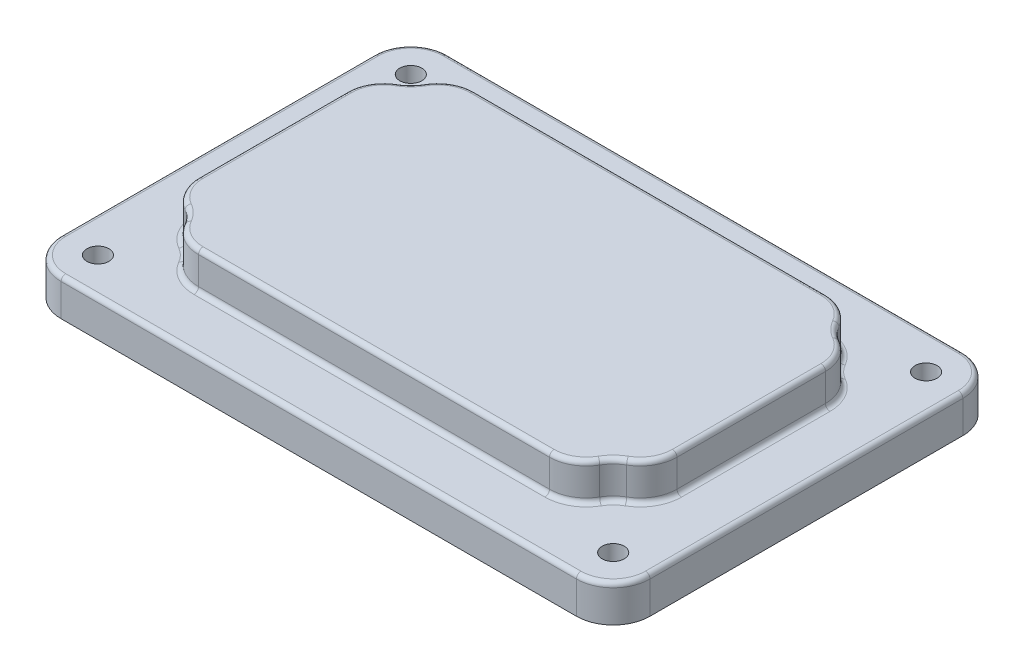
SolidWorks part; units mm, degrees
material "Cast Alloy Steel"
ref_plane "Front Plane" through (0, 0, 0) normal (0, 0, 1) x (1, 0, 0)
ref_plane "Top Plane" through (0, 0, 0) normal (0, 1, 0) x (1, 0, 0)
ref_plane "Right Plane" through (0, 0, 0) normal (1, 0, 0) x (0, 0, -1)
sketch "Sketch1" plane through (0, 0, 0) normal (0, 1, 0) x (1, 0, 0)
  line L1 (-44.45, 33.3375) -> (44.45, 33.3375)
  line L2 (-50.8, 26.9875) -> (-50.8, -26.9875)
  line L3 (-44.45, -33.3375) -> (44.45, -33.3375)
  line L4 (50.8, 26.9875) -> (50.8, -26.9875)
  line L5 (-50.8, 33.3375) -> (50.8, -33.3375) construction
  line L6 (-50.8, -33.3375) -> (50.8, 33.3375) construction
  arc A0 (44.45, -33.3375) -> (50.8, -26.9875) centre (44.45, -26.9875) ccw
  arc A1 (44.45, 33.3375) -> (50.8, 26.9875) centre (44.45, 26.9875) cw
  arc A2 (-44.45, 33.3375) -> (-50.8, 26.9875) centre (-44.45, 26.9875) ccw
  arc A3 (-50.8, -26.9875) -> (-44.45, -33.3375) centre (-44.45, -26.9875) ccw
  point P0 (0, 0)
  dimension "D3" = 6.35
  dimension "D1" = 66.675
  dimension "D2" = 101.6
extrude "Base" add sketch "Sketch1" along normal blind 6.35
sketch "Sketch2" plane through (0, 6.35, 0) normal (0, 1, 0) x (1, 0, 0)
  line L8 (41.275, -23.8125) -> (41.275, 23.8125)
  line L9 (41.275, 23.8125) -> (-41.275, 23.8125)
  line L10 (-41.275, 23.8125) -> (-41.275, -23.8125)
  line L11 (-41.275, -23.8125) -> (41.275, -23.8125)
  line L12 (41.275, -23.8125) -> (41.275, 23.8125)
  line L13 (41.275, 23.8125) -> (-41.275, 23.8125)
  line L14 (-41.275, 23.8125) -> (-41.275, -23.8125)
  line L15 (-41.275, -23.8125) -> (41.275, -23.8125)
  dimension "D1" = 9.525
extrude "Top Boss" add sketch "Sketch2" along normal blind 6.35
sketch "Sketch3" plane through (0, 12.7, 0) normal (0, 1, 0) x (1, 0, 0)
  line L0 (0, 0) -> (60.3016, 0) construction
  line L1 (0, 0) -> (0, 40.0067) construction
  circle A0 centre (41.275, 23.8125) radius 6.35
  circle A1 centre (-41.275, 23.8125) radius 6.35
  circle A2 centre (-41.275, -23.8125) radius 6.35
  circle A3 centre (41.275, -23.8125) radius 6.35
  dimension "D1" = 12.7
extrude "Corner Cuts" cut sketch "Sketch3" against normal up to surface (6.35 mm away) up to face at (0, 6.35, 0)
fillet "Fillet1" radius 6.35 8 edges at (34.925, 9.525, 23.8125) (41.275, 9.525, 17.4625) (41.275, 9.525, -17.4625) (34.925, 9.525, -23.8125) (-34.925, 9.525, -23.8125) (-41.275, 9.525, -17.4625) (-41.275, 9.525, 17.4625) (-34.925, 9.525, 23.8125)
shell "Shell1" thickness 3.175
sketch "Sketch4" plane through (0, 0, 0) normal (0, -1, 0) x (1, 0, 0)
  circle A0 centre (-44.45, 26.9875) radius 6.35
  circle A1 centre (44.45, 26.9875) radius 6.35
  circle A2 centre (44.45, -26.9875) radius 6.35
  circle A3 centre (-44.45, -26.9875) radius 6.35
  arc A4 (-50.8, -26.9875) -> (-44.45, -33.3375) centre (-44.45, -26.9875) ccw construction
extrude "Boss-Extrude3" add sketch "Sketch4" against normal up to surface (3.175 mm away) up to face at (0, 3.175, 0)
fillet "Fillet2" radius 0.7874 40 edges at (0, 6.35, 33.3375) (-48.9401, 6.35, 31.4776) (-50.8, 6.35, 0) (-48.9401, 6.35, -31.4776) (0, 6.35, -33.3375) (48.9401, 6.35, -31.4776) (50.8, 6.35, 0) (48.9401, 6.35, 31.4776) (-40.4243, 6.35, 15.989) (-36.7849, 12.7, 19.3224) (-36.7849, 6.35, 19.3224) (-33.4515, 6.35, 22.9618) (0, 6.35, 23.8125) (33.4515, 6.35, 22.9618) (36.7849, 12.7, 19.3224) (36.7849, 6.35, 19.3224) (40.4243, 6.35, 15.989) (41.275, 6.35, 0) (40.4243, 6.35, -15.989) (36.7849, 12.7, -19.3224) (36.7849, 6.35, -19.3224) (33.4515, 6.35, -22.9618) (0, 6.35, -23.8125) (-33.4515, 6.35, -22.9618) (-36.7849, 12.7, -19.3224) (-36.7849, 6.35, -19.3224) (-40.4243, 6.35, -15.989) (-41.275, 6.35, 0) (-33.4515, 12.7, 22.9618) (-40.4243, 12.7, 15.989) (-41.275, 12.7, 0) (-40.4243, 12.7, -15.989) (-33.4515, 12.7, -22.9618) (0, 12.7, -23.8125) (33.4515, 12.7, -22.9618) (40.4243, 12.7, -15.989) (41.275, 12.7, 0) (40.4243, 12.7, 15.989) (33.4515, 12.7, 22.9618) (0, 12.7, 23.8125)
fillet "Fillet3" radius 0.7874 56 edges at (39.9599, 0, -22.4974) (39.9599, 3.175, -22.4974) (-39.9599, 0, -22.4974) (-39.9599, 3.175, -22.4974) (-39.9599, 0, 22.4974) (-39.9599, 3.175, 22.4974) (39.9599, 3.175, 22.4974) (39.9599, 0, 22.4974) (47.625, 3.175, 0) (47.625, 1.5875, 21.4882) (47.625, 0, 0) (47.625, 1.5875, -21.4882) (0, 3.175, -30.1625) (38.9507, 1.5875, -30.1625) (0, 0, -30.1625) (-38.9507, 1.5875, -30.1625) (-47.625, 0, 0) (-47.625, 1.5875, 21.4882) (-47.625, 3.175, 0) (-47.625, 1.5875, -21.4882) (0, 3.175, 30.1625) (-38.9507, 1.5875, 30.1625) (0, 0, 30.1625) (38.9507, 1.5875, 30.1625) (0, 3.175, 20.6375) (38.1, 3.175, 0) (0, 3.175, -20.6375) (-38.1, 3.175, 0) (38.1, 9.525, 0) (0, 9.525, -20.6375) (-38.1, 9.525, 0) (0, 9.525, 20.6375) (34.5398, 3.175, -17.0773) (34.5398, 9.525, -17.0773) (34.5398, 3.175, 17.0773) (34.5398, 9.525, 17.0773) (-34.5398, 3.175, 17.0773) (-34.5398, 9.525, 17.0773) (-34.5398, 3.175, -17.0773) (-34.5398, 9.525, -17.0773) (31.864, 9.525, 20.2121) (31.864, 3.175, 20.2121) (37.6746, 3.175, 14.4015) (37.6746, 9.525, 14.4015) (37.6746, 9.525, -14.4015) (37.6746, 3.175, -14.4015) (31.864, 3.175, -20.2121) (31.864, 9.525, -20.2121) (-31.864, 9.525, -20.2121) (-31.864, 3.175, -20.2121) (-37.6746, 3.175, -14.4015) (-37.6746, 9.525, -14.4015) (-37.6746, 9.525, 14.4015) (-37.6746, 3.175, 14.4015) (-31.864, 3.175, 20.2121) (-31.864, 9.525, 20.2121)
hole_wizard "#6 Clearance Hole1" positions "Sketch5" profile "Sketch6" hole size "#6" standard "ANSI Inch" end condition through all
sketch "Sketch5" plane through (0, 6.35, 0) normal (0, 1, 0) x (1, 0, 0)
  point P0 (-44.45, 26.9875)
  point P3 (44.45, 26.9875)
  point P6 (44.45, -26.9875)
  point P9 (-44.45, -26.9875)
sketch "Sketch6" plane through (-44.45, 6.35, -26.9875) normal (1, 0, 0) x (0, 0, 1)
  line L0 (0, 0) -> (0, 6.35)
  line L1 (0, 6.35) -> (1.8986, 6.35)
  line L2 (1.8986, 6.35) -> (1.8986, 0)
  line L5 (1.8986, 0) -> (0, 0)
  line L11 (0, -6.35) -> (0, 107.95) construction
  dimension "Thru Hole Dia." = 3.7973
  dimension "Thru Hole Depth" = 6.35
